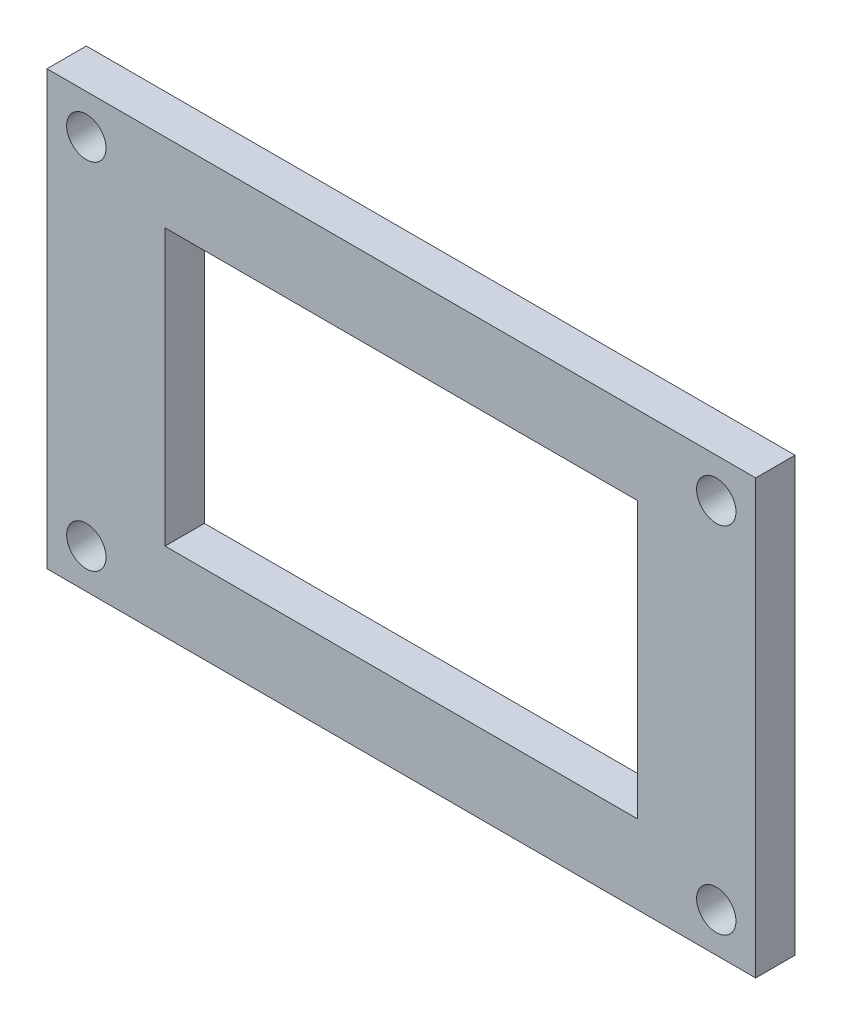
SolidWorks part; units mm, degrees
ref_plane "Front Plane" through (0, 0, 0) normal (0, 0, 1) x (1, 0, 0)
ref_plane "Top Plane" through (0, 0, 0) normal (0, 1, 0) x (1, 0, 0)
ref_plane "Right Plane" through (0, 0, 0) normal (1, 0, 0) x (0, 0, -1)
sketch "Sketch1" plane through (0, 0, 0) normal (0, 0, 1) x (1, 0, 0)
  line L1 (-28.575, -17.4625) -> (28.575, -17.4625)
  line L2 (-28.575, -17.4625) -> (-28.575, 17.4625)
  line L3 (-28.575, 17.4625) -> (28.575, 17.4625)
  line L4 (28.575, -17.4625) -> (28.575, 17.4625)
  line L5 (-28.575, -17.4625) -> (28.575, 17.4625) construction
  line L6 (-28.575, 17.4625) -> (28.575, -17.4625) construction
  line L7 (19.05, -11.1125) -> (-19.05, -11.1125)
  line L8 (19.05, -11.1125) -> (19.05, 11.1125)
  line L9 (19.05, 11.1125) -> (-19.05, 11.1125)
  line L10 (-19.05, -11.1125) -> (-19.05, 11.1125)
  line L11 (19.05, -11.1125) -> (-19.05, 11.1125) construction
  line L12 (19.05, 11.1125) -> (-19.05, -11.1125) construction
  point P0 (0, 0)
  point P6 (0, 0)
  dimension "D1" = 57.15
  dimension "D2" = 34.925
  dimension "D3" = 22.225
  dimension "D4" = 38.1
extrude "Boss-Extrude1" add sketch "Sketch1" along normal blind 3.175
sketch "Sketch2" plane through (0, 0, 0) normal (0, 0, -1) x (-1, 0, 0)
  line L4 (-25.4, 14.2875) -> (25.4, 14.2875) construction
  line L5 (25.4, 14.2875) -> (25.4, -14.2875) construction
  line L6 (25.4, -14.2875) -> (-25.4, -14.2875) construction
  line L7 (-25.4, -14.2875) -> (-25.4, 14.2875) construction
  line L8 (-28.575, -17.4625) -> (-28.575, 17.4625) construction
  line L9 (28.575, 17.4625) -> (28.575, -17.4625) construction
  line L10 (-28.575, 17.4625) -> (28.575, 17.4625) construction
  line L11 (28.575, -17.4625) -> (-28.575, -17.4625) construction
  circle A0 centre (-25.4, -14.2875) radius 1.5875
  circle A1 centre (-25.4, 14.2875) radius 1.5875
  circle A2 centre (25.4, 14.2875) radius 1.5875
  circle A3 centre (25.4, -14.2875) radius 1.5875
  dimension "D5" = 3.175
  dimension "D1" = 3.175
  dimension "D2" = 3.175
  dimension "D3" = 3.175
  dimension "D4" = 3.175
extrude "Cut-Extrude1" cut sketch "Sketch2" against normal blind 3.175
